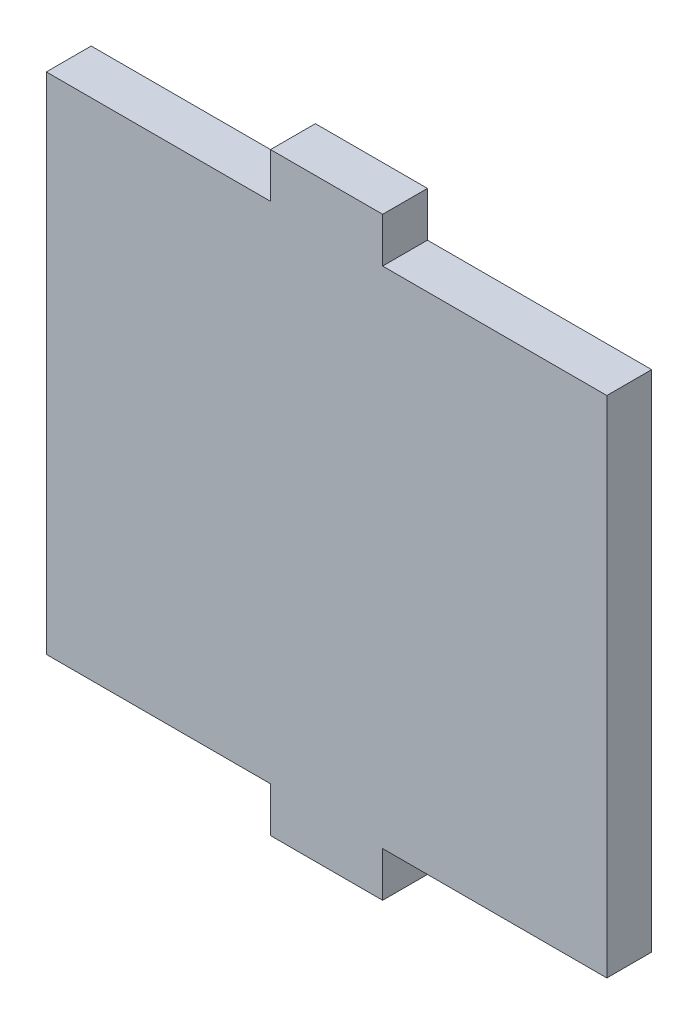
SolidWorks part; units mm, degrees
ref_plane "Front Plane" through (0, 0, 0) normal (0, 0, 1) x (1, 0, 0)
ref_plane "Top Plane" through (0, 0, 0) normal (0, 1, 0) x (1, 0, 0)
ref_plane "Right Plane" through (0, 0, 0) normal (1, 0, 0) x (0, 0, -1)
sketch "Esquisse1" plane through (0, 0, 0) normal (0, 0, 1) x (1, 0, 0)
  line L1 (50, 0) -> (50, -45)
  line L2 (50, -45) -> (30, -45)
  line L3 (30, -45) -> (30, -49)
  line L4 (30, -49) -> (20, -49)
  line L5 (20, -49) -> (20, -45)
  line L6 (20, -45) -> (0, -45)
  line L7 (0, -45) -> (0, 0)
  line L8 (0, 0) -> (20, 0)
  line L9 (20, 0) -> (20, 4)
  line L10 (20, 4) -> (30, 4)
  line L11 (30, 4) -> (30, 0)
  line L12 (30, 0) -> (50, 0)
  dimension "D1" = 4
  dimension "D2" = 4
  dimension "D3" = 20
  dimension "D4" = 20
  dimension "D5" = 10
  dimension "D7" = 45
extrude "Boss.-Extru.1" add sketch "Esquisse1" along normal blind 4
